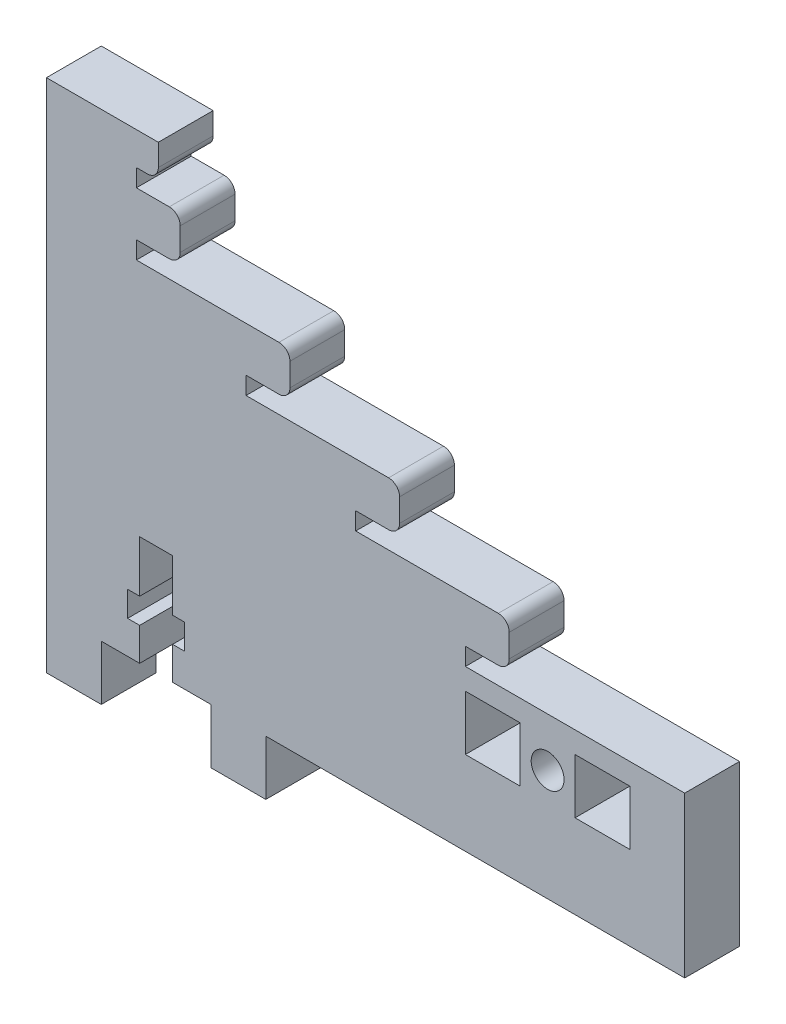
SolidWorks part; units mm, degrees
ref_plane "Front Plane" through (0, 0, 0) normal (0, 0, 1) x (1, 0, 0)
ref_plane "Top Plane" through (0, 0, 0) normal (0, 1, 0) x (1, 0, 0)
ref_plane "Right Plane" through (0, 0, 0) normal (1, 0, 0) x (0, 0, -1)
sketch "Sketch1" plane through (0, 0, 0) normal (0, 0, 1) x (1, 0, 0)
  line L0 (0, 5) -> (0, 19.9828)
  line L1 (20, 5) -> (20, 19.6) construction
  line L3 (28.2, 25.3) -> (28.2, 26.9)
  line L4 (28.2, 26.9) -> (32.2, 26.9)
  line L5 (32.2, 26.9) -> (32.2, 31)
  line L7 (0, 31) -> (0, 19.9828)
  line L8 (10, 5) -> (10, 15.0197) construction
  line L9 (8.5, 5) -> (5, 5)
  line L10 (5, 0) -> (0, 0)
  line L11 (0, 0) -> (0, 5)
  line L12 (5, 0) -> (5, 5)
  line L13 (11.5, 5) -> (15, 5)
  line L14 (15, 5) -> (15, 0)
  line L15 (15, 0) -> (20, 0)
  line L16 (20, 0) -> (20, 5)
  line L17 (8.5, 5) -> (11.5, 5) construction
  line L18 (11.5, 5) -> (11.5, 8)
  line L19 (11.5, 10.3) -> (12.6, 10.3)
  line L20 (7.4, 8) -> (7.4, 10.3)
  line L21 (12.6, 8) -> (11.5, 8)
  line L22 (11.5, 10.3) -> (11.5, 15)
  line L23 (11.5, 15) -> (8.5, 15)
  line L24 (8.5, 15) -> (8.5, 10.3)
  line L25 (8.5, 8) -> (7.4, 8)
  line L26 (12.6, 10.3) -> (12.6, 8)
  line L27 (7.4, 10.3) -> (8.5, 10.3)
  line L28 (8.5, 8) -> (8.5, 5)
  line L29 (10, 15) -> (10, 5) construction
  line L30 (32.2, 31) -> (18.2, 31)
  line L31 (18.2, 31) -> (18.2, 32.6)
  line L32 (18.2, 32.6) -> (22.2, 32.6)
  line L33 (22.2, 32.6) -> (22.2, 36.7)
  line L35 (0, 30.1) -> (0, 31)
  line L37 (58.2, 25.3) -> (58.2, 5) construction
  line L38 (58.2, 5) -> (20, 5)
  line L39 (22.2, 36.7) -> (8.2, 36.7)
  line L40 (8.2, 36.7) -> (8.2, 38.3)
  line L41 (8.2, 38.3) -> (12.2, 38.3)
  line L47 (10.2, 47) -> (0, 47)
  line L48 (0, 47) -> (0, 30.1)
  line L49 (12.2, 38.3) -> (12.2, 42.4)
  line L50 (12.2, 42.4) -> (8.2, 42.4)
  line L51 (8.2, 42.4) -> (8.2, 44)
  line L52 (8.2, 44) -> (10.2, 44)
  line L53 (10.2, 44) -> (10.2, 47)
  line L54 (28.2, 25.3) -> (58.2, 25.3) construction
  line L55 (58.2, 15.15) -> (32.0391, 15.15) construction
  line L56 (28.2, 25.3) -> (42.2, 25.3)
  line L57 (42.2, 25.3) -> (42.2, 21.2)
  line L58 (42.2, 21.2) -> (38.2, 21.2)
  line L59 (38.2, 21.2) -> (38.2, 19.6)
  line L60 (38.2, 19.6) -> (58.2, 19.6)
  line L61 (58.2, 19.6) -> (58.2, 5)
  point P41 (8.2, 43.2)
  line B0 (43.2, 15.15) -> (48.2, 15.15) construction
  line B1 (43.2, 17.65) -> (38.2, 17.65)
  line B2 (43.2, 17.65) -> (43.2, 12.65)
  line B3 (43.2, 12.65) -> (38.2, 12.65)
  line B4 (38.2, 17.65) -> (38.2, 12.65)
  line B5 (48.2, 17.65) -> (53.2, 17.65)
  line B6 (48.2, 17.65) -> (48.2, 12.65)
  line B7 (48.2, 12.65) -> (53.2, 12.65)
  line B8 (53.2, 17.65) -> (53.2, 12.65)
  line B9 (45.7, 15.15) -> (45.7, 22.1224) construction
  circle B10 centre (45.7, 15.15) radius 1.5
  dimension "D2" = 20.3
  dimension "D3" = 4
  dimension "D4" = 5.7
  dimension "D5" = 10
  dimension "D6" = 5
  dimension "D7" = 5
  dimension "D8" = 5.2
  dimension "D9" = 3
  dimension "D10" = 2.3
  dimension "D11" = 3
  dimension "D12" = 10
  dimension "D13" = 8.2
  dimension "D14" = 10
  dimension "D15" = 2
  dimension "D16" = 1.6
  dimension "D17" = 10
  dimension "D18" = 5.7
  dimension "D19" = 3
  dimension "D20" = 5
  dimension "D21" = 10
  dimension "D22" = 5.7
sketch_block_instance "Trou M3 plots 5mm Ecartement Reduit-3"
sketch_block "Trou M3 plots 5mm Ecartement Reduit" parameters "D2"=3, "D1"=5, "D3"=5, "D4"=5
extrude "Boss-Extrude1" add sketch "Sketch1" along normal blind 5 contours L61 L60 L59 L58 L57 L56 L3 L4 L5 L30 L31 L32 L33 L39 L40 L41 L49 L50 L51 L52 L53 L47 L48 L7 L0 L11 L10 L12 L9 L28 L25 L20 L27 L24 L23 L22 L19 L26 L21 L18 L13 L14 L15 L16 L38 B10 B4 B1
fillet "Fillet3" radius 1 9 edges at (32.2, 26.9, 2.5) (10.2, 44, 2.5) (12.2, 38.3, 2.5) (12.2, 42.4, 2.5) (22.2, 32.6, 2.5) (22.2, 36.7, 2.5) (32.2, 31, 2.5) (42.2, 25.3, 2.5) (42.2, 21.2, 2.5)
